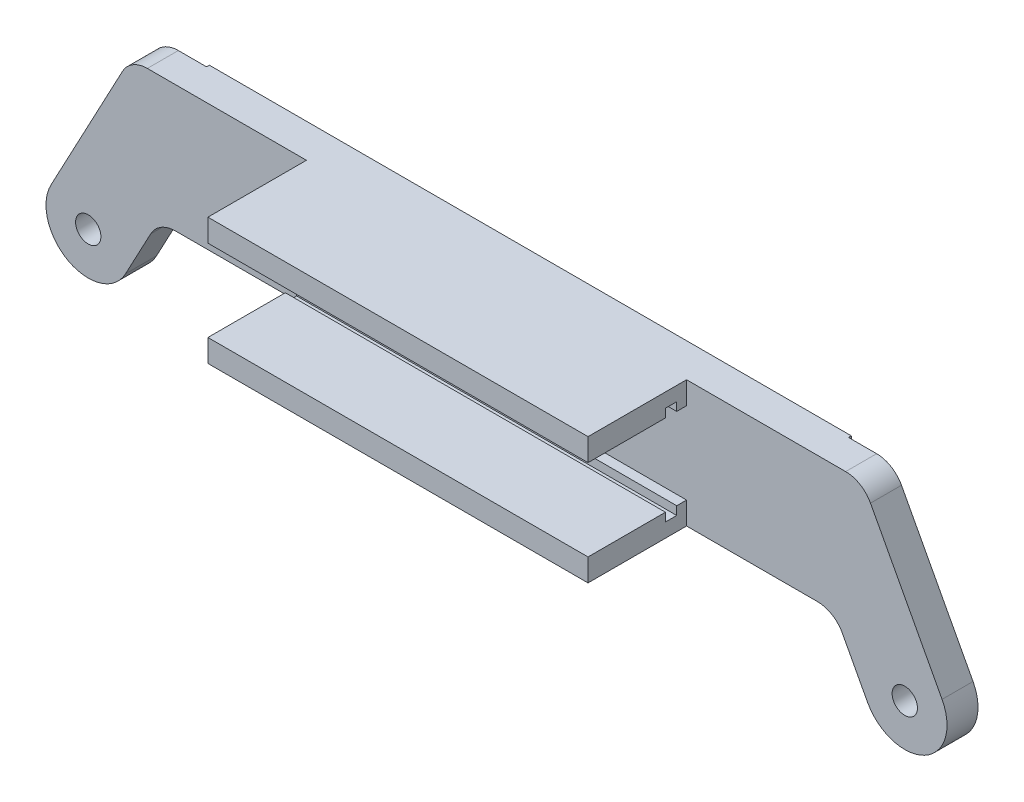
SolidWorks part; units mm, degrees
ref_plane "前视基准面" through (0, 0, 0) normal (0, 0, 1) x (1, 0, 0)
ref_plane "上视基准面" through (0, 0, 0) normal (0, 1, 0) x (1, 0, 0)
ref_plane "右视基准面" through (0, 0, 0) normal (1, 0, 0) x (0, 0, -1)
sketch "草图1" plane through (0, 0, 0) normal (0, 0, 1) x (1, 0, 0)
  line L1 (110, -22.5) -> (-110, -22.5)
  line L2 (110, -22.5) -> (110, 22.5)
  line L3 (110, 22.5) -> (-110, 22.5)
  line L4 (-110, -22.5) -> (-110, 22.5)
  line L5 (110, -22.5) -> (-110, 22.5) construction
  line L6 (110, 22.5) -> (-110, -22.5) construction
  point P0 (0, 0)
  dimension "D1" = 45
  dimension "D2" = 220
extrude "凸台-拉伸1" add sketch "草图1" along normal blind 6
sketch "草图2" plane through (0, 0, 6) normal (0, 0, 1) x (1, 0, 0)
  line L1 (-77.5, 22.5) -> (77.5, 22.5)
  line L8 (110, 22.5) -> (-110, 22.5) construction
  line L12 (-110, -22.5) -> (110, -22.5) construction
  line L15 (-77.5, 22.5) -> (-77.5, 14.5)
  line L16 (-75, 14.5) -> (75, 14.5)
  line L17 (-75, -14.5) -> (75, -14.5)
  line L18 (-77.5, 14.5) -> (-75, 14.5)
  line L20 (77.5, 22.5) -> (77.5, 14.5)
  line L21 (77.5, 14.5) -> (75, 14.5)
  line L22 (-77.5, -22.5) -> (-77.5, -14.5)
  line L23 (-77.5, -14.5) -> (-75, -14.5)
  line L24 (77.5, -22.5) -> (77.5, -14.5)
  line L25 (77.5, -14.5) -> (75, -14.5)
  line L26 (-77.5, -22.5) -> (77.5, -22.5)
extrude "凸台-拉伸2" add sketch "草图2" along normal blind 35
sketch "草图5" plane through (-77.5, 0, 0) normal (-1, 0, 0) x (0, 0, 1)
  line L0 (6, 0) -> (12.083, 0) construction
  line L2 (6, 22.5) -> (6, -22.5) construction
  line L3 (9.5, -14.5) -> (9.5, -17.5)
  line L4 (9.5, 17.5) -> (13.5, 17.5)
  line L5 (13.5, 17.5) -> (13.5, 14.5)
  line L6 (41, 14.5) -> (6, 14.5) construction
  line L7 (13.5, 14.5) -> (9.5, 14.5)
  line L8 (9.5, 14.5) -> (9.5, 17.5)
  line L9 (13.5, -14.5) -> (9.5, -14.5)
  line L10 (13.5, -17.5) -> (13.5, -14.5)
  line L11 (9.5, -17.5) -> (13.5, -17.5)
  dimension "D3" = 4
extrude "切除-拉伸3" cut sketch "草图5" against normal through all
sketch "草图6" plane through (0, 0, 0) normal (0, 0, -1) x (-1, 0, 0)
  line L0 (-110, 22.5) -> (-110, -22.5)
  line L1 (-110, -22.5) -> (110, -22.5)
  line L2 (110, -22.5) -> (110, 22.5)
  line L3 (110, 22.5) -> (-110, 22.5)
extrude "凸台-拉伸3" add sketch "草图6" along normal blind 5
sketch "草图9" plane through (0, 0, -5) normal (0, 0, -1) x (-1, 0, 0)
  line L0 (-110, -22.5) -> (-110, 22.5)
  line L2 (-110, 22.5) -> (-130, 22.5)
  line L3 (-110, -22.5) -> (-120, -22.5)
  line L4 (-120, -22.5) -> (-131.7647, -44.5588)
  line L5 (-158.2353, -30.4412) -> (-130, 22.5)
  arc A0 (-158.2353, -30.4412) -> (-131.7647, -44.5588) centre (-145, -37.5) ccw
  dimension "D3" = 30
  dimension "D1" = 60
  dimension "D2" = 20
  dimension "D4" = 10
extrude "凸台-拉伸4" add sketch "草图9" against normal blind 11
sketch "草图10" plane through (0, 0, 6) normal (0, 0, 1) x (1, 0, 0)
  circle A0 centre (145, -37.5) radius 4.5
  dimension "D1" = 9
extrude "切除-拉伸4" cut sketch "草图10" against normal through all
mirror "镜向1" about plane through (0, 0, 0) normal (1, 0, 0) of "切除-拉伸4", "凸台-拉伸4"
fillet "圆角1" radius 10 4 edges at (-120, -22.5, 0.5) (-130, 22.5, 0.5) (130, 22.5, 0.5) (120, -22.5, 0.5)
sketch "草图11" plane through (0, 0, 41) normal (0, 0, 1) x (1, 0, 0)
  line L0 (-77.5, 22.5) -> (-77.5, 14.5)
  line L1 (-77.5, 14.5) -> (-67.5, 14.5)
  line L2 (-77.5, 14.5) -> (77.5, 14.5) construction
  line L3 (-67.5, 14.5) -> (-67.5, 22.5)
  line L4 (77.5, 22.5) -> (-77.5, 22.5) construction
  line L5 (-67.5, 22.5) -> (-77.5, 22.5)
  line L6 (0, 0) -> (0, 9.6747) construction
  line L7 (0, 0) -> (-19.3695, 0) construction
  line L8 (67.5, 14.5) -> (67.5, 22.5)
  line L9 (77.5, 14.5) -> (67.5, 14.5)
  line L10 (77.5, 22.5) -> (77.5, 14.5)
  line L11 (67.5, 22.5) -> (77.5, 22.5)
  line L12 (77.5, -14.5) -> (67.5, -14.5)
  line L13 (77.5, -22.5) -> (77.5, -14.5)
  line L14 (67.5, -22.5) -> (77.5, -22.5)
  line L15 (67.5, -14.5) -> (67.5, -22.5)
  line L16 (-67.5, -14.5) -> (-67.5, -22.5)
  line L17 (-77.5, -14.5) -> (-67.5, -14.5)
  line L18 (-77.5, -22.5) -> (-77.5, -14.5)
  line L19 (-67.5, -22.5) -> (-77.5, -22.5)
  dimension "D1" = 10
extrude "切除-拉伸6" cut sketch "草图11" against normal blind 35
sketch "草图18" plane through (0, 0, -5) normal (0, 0, -1) x (-1, 0, 0)
  line L0 (-114, 22.5) -> (114, 22.5)
  line L1 (124, 22.5) -> (-124, 22.5) construction
  line L2 (-114, 22.5) -> (-114, -22.5)
  line L3 (-114, -22.5) -> (114, -22.5)
  line L4 (114, -22.5) -> (114, 22.5)
extrude "凸台-拉伸5" add sketch "草图18" along normal blind 1
